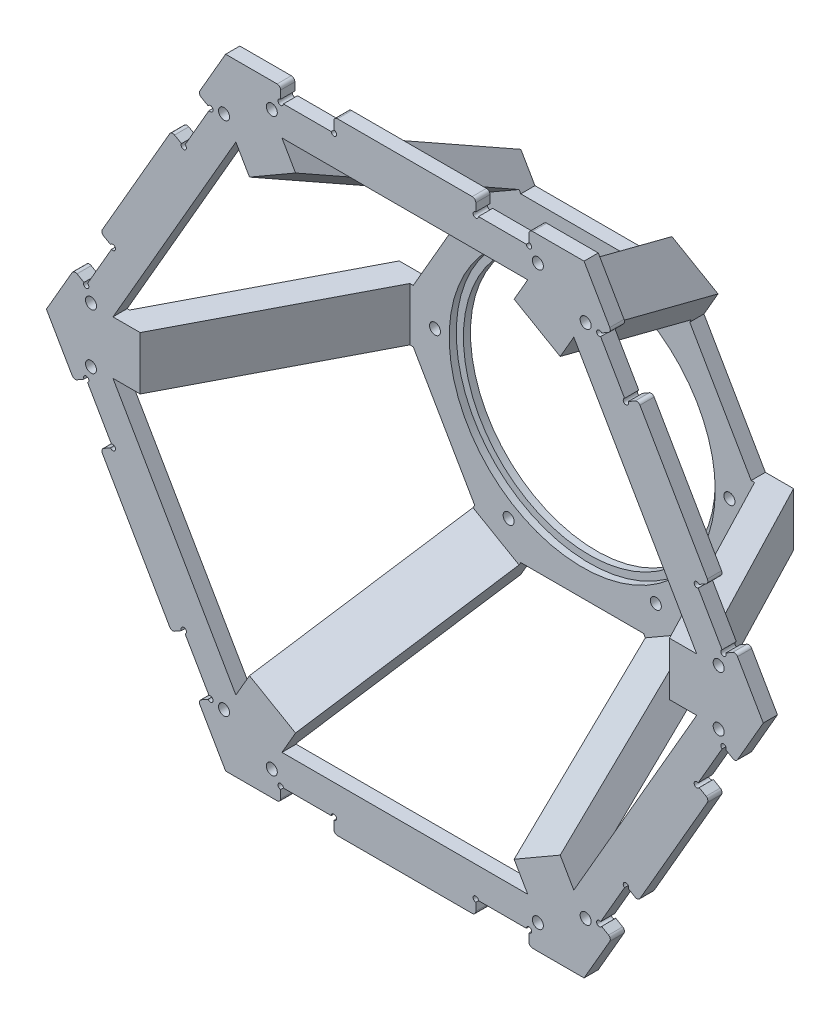
SolidWorks part; units mm, degrees
other "Markup1"
sketch "Sketch62" plane through (-128.5, -128.5, 146.8) normal (-0.0672, -0.6619, 0.7466) x (0.996, 0, 0.0896)
other "Markup2"
sketch "Sketch87" plane through (-128.5, 200.1498, -230) normal (-0.7911, 0.6051, -0.0891) x (-0.112, 0, 0.9937)
ref_plane "Front" through (0, 0, 0) normal (0, 0, 1) x (1, 0, 0)
ref_plane "Top" through (0, 0, 0) normal (0, 1, 0) x (1, 0, 0)
ref_plane "Right" through (0, 0, 0) normal (1, 0, 0) x (0, 0, -1)
sketch "Sketch48" plane through (0, 0, 0) normal (0, 0, 1) x (1, 0, 0)
  line L32 (109.6966, 0) -> (54.8483, 95)
  line L33 (54.8483, 95) -> (-54.8483, 95)
  line L34 (-54.8483, 95) -> (-109.6966, 0)
  line L69 (-109.6966, 0) -> (-54.8483, -95)
  line L70 (-54.8483, -95) -> (54.8483, -95)
  line L71 (54.8483, -95) -> (109.6966, 0)
  circle A2 centre (0, 0) radius 35.5
  circle A13 centre (0, 0) radius 95 construction
  dimension "D1" = 190
  dimension "D8" = 71
extrude "Boss-Extrude15" add sketch "Sketch48" along normal blind 4 separate body
sketch "Sketch88" plane through (0, 0, 4) normal (0, 0, 1) x (1, 0, 0)
  line L0 (0, 0) -> (0, 98.5261) construction
  line L1 (20, 87.5) -> (35, 87.5)
  line L2 (20, 87.5) -> (20, 83.5)
  line L3 (20, 83.5) -> (35, 83.5)
  line L4 (35, 87.5) -> (35, 83.5)
  line L5 (-35, 87.5) -> (-35, 83.5)
  line L6 (-20, 83.5) -> (-35, 83.5)
  line L7 (-20, 87.5) -> (-20, 83.5)
  line L8 (-20, 87.5) -> (-35, 87.5)
  line L9 (58.2772, 74.0609) -> (54.8131, 72.0609)
  line L10 (62.3131, 59.0705) -> (54.8131, 72.0609)
  line L11 (65.7772, 61.0705) -> (62.3131, 59.0705)
  line L12 (65.7772, 61.0705) -> (58.2772, 74.0609)
  line L13 (85.7772, 26.4295) -> (82.3131, 24.4295)
  line L14 (85.7772, 26.4295) -> (93.2772, 13.4391)
  line L15 (93.2772, 13.4391) -> (89.8131, 11.4391)
  line L16 (82.3131, 24.4295) -> (89.8131, 11.4391)
  line L17 (93.2772, -13.4391) -> (89.8131, -11.4391)
  line L18 (82.3131, -24.4295) -> (89.8131, -11.4391)
  line L19 (85.7772, -26.4295) -> (82.3131, -24.4295)
  line L20 (85.7772, -26.4295) -> (93.2772, -13.4391)
  line L21 (65.7772, -61.0705) -> (62.3131, -59.0705)
  line L22 (65.7772, -61.0705) -> (58.2772, -74.0609)
  line L23 (58.2772, -74.0609) -> (54.8131, -72.0609)
  line L24 (62.3131, -59.0705) -> (54.8131, -72.0609)
  line L25 (35, -87.5) -> (35, -83.5)
  line L26 (20, -83.5) -> (35, -83.5)
  line L27 (20, -87.5) -> (20, -83.5)
  line L28 (20, -87.5) -> (35, -87.5)
  line L29 (-20, -87.5) -> (-20, -83.5)
  line L30 (-20, -87.5) -> (-35, -87.5)
  line L31 (-35, -87.5) -> (-35, -83.5)
  line L32 (-20, -83.5) -> (-35, -83.5)
  line L33 (-58.2772, -74.0609) -> (-54.8131, -72.0609)
  line L34 (-62.3131, -59.0705) -> (-54.8131, -72.0609)
  line L35 (-65.7772, -61.0705) -> (-62.3131, -59.0705)
  line L36 (-65.7772, -61.0705) -> (-58.2772, -74.0609)
  line L37 (-85.7772, -26.4295) -> (-82.3131, -24.4295)
  line L38 (-85.7772, -26.4295) -> (-93.2772, -13.4391)
  line L39 (-93.2772, -13.4391) -> (-89.8131, -11.4391)
  line L40 (-82.3131, -24.4295) -> (-89.8131, -11.4391)
  line L41 (-93.2772, 13.4391) -> (-89.8131, 11.4391)
  line L42 (-82.3131, 24.4295) -> (-89.8131, 11.4391)
  line L43 (-85.7772, 26.4295) -> (-82.3131, 24.4295)
  line L44 (-85.7772, 26.4295) -> (-93.2772, 13.4391)
  line L45 (-65.7772, 61.0705) -> (-62.3131, 59.0705)
  line L46 (-65.7772, 61.0705) -> (-58.2772, 74.0609)
  line L47 (-58.2772, 74.0609) -> (-54.8131, 72.0609)
  line L48 (-62.3131, 59.0705) -> (-54.8131, 72.0609)
  line L49 (0, 0) -> (-53.5159, 0) construction
  circle A0 centre (-37.5, 80.5) radius 1.55
  circle A1 centre (37.5, 80.5) radius 1.55
  circle A2 centre (50.965, 72.726) radius 1.55
  circle A3 centre (88.465, 7.774) radius 1.55
  circle A4 centre (88.465, -7.774) radius 1.55
  circle A5 centre (50.965, -72.726) radius 1.55
  circle A6 centre (37.5, -80.5) radius 1.55
  circle A7 centre (-37.5, -80.5) radius 1.55
  circle A8 centre (-50.965, -72.726) radius 1.55
  circle A9 centre (-88.465, -7.774) radius 1.55
  circle A10 centre (-88.465, 7.774) radius 1.55
  circle A11 centre (-50.965, 72.726) radius 1.55
  point P7 (27.5, 83.5)
  point P14 (-27.5, 83.5)
  point P55 (0, 0)
  dimension "D6" = 3
  dimension "D7" = 3.1
  dimension "D8" = 10
  dimension "D1" = 4
  dimension "D2" = 15
  dimension "D3" = 55
  dimension "D4" = 87.5
  dimension "D5" = 6
  dimension "D9" = 6
extrude "Cut-Extrude1" cut sketch "Sketch88" against normal through all
sketch "Sketch89" plane through (0, 0, 4) normal (0, 0, 1) x (1, 0, 0)
  circle A0 centre (0, 0) radius 37.5
  dimension "D1" = 75
extrude "Cut-Extrude2" cut sketch "Sketch89" against normal blind 2
sketch "Sketch90" plane through (0, 0, 4) normal (0, 0, 1) x (1, 0, 0)
  line L2 (0, 0) -> (0, 110.1203) construction
  line L3 (0, 0) -> (49.6986, 0) construction
  circle A1 centre (-35, 83.5) radius 0.75
  circle A3 centre (-20, 83.5) radius 0.75
  circle A4 centre (20, 83.5) radius 0.75
  circle A6 centre (35, 83.5) radius 0.75
  circle A9 centre (54.8131, 72.0609) radius 0.75
  circle A11 centre (62.3131, 59.0705) radius 0.75
  circle A13 centre (82.3131, 24.4295) radius 0.75
  circle A15 centre (89.8131, 11.4391) radius 0.75
  circle A17 centre (89.8131, -11.4391) radius 0.75
  circle A19 centre (82.3131, -24.4295) radius 0.75
  circle A21 centre (62.3131, -59.0705) radius 0.75
  circle A23 centre (54.8131, -72.0609) radius 0.75
  circle A25 centre (35, -83.5) radius 0.75
  circle A27 centre (20, -83.5) radius 0.75
  circle A29 centre (-20, -83.5) radius 0.75
  circle A31 centre (-35, -83.5) radius 0.75
  circle A33 centre (-54.8131, -72.0609) radius 0.75
  circle A35 centre (-62.3131, -59.0705) radius 0.75
  circle A37 centre (-82.3131, -24.4295) radius 0.75
  circle A39 centre (-89.8131, -11.4391) radius 0.75
  circle A41 centre (-89.8131, 11.4391) radius 0.75
  circle A43 centre (-82.3131, 24.4295) radius 0.75
  circle A45 centre (-62.3131, 59.0705) radius 0.75
  circle A47 centre (-54.8131, 72.0609) radius 0.75
  circle A48 centre (41.5, 0) radius 1.55
  circle A49 centre (20.75, -35.9401) radius 1.55
  circle A50 centre (-20.75, -35.9401) radius 1.55
  circle A51 centre (-41.5, 0) radius 1.55
  circle A52 centre (-20.75, 35.9401) radius 1.55
  circle A53 centre (20.75, 35.9401) radius 1.55
  dimension "D1" = 1.5
  dimension "D3" = 41.5
  dimension "D4" = 3.1
  dimension "D2" = 6
  dimension "D5" = 6
extrude "Cut-Extrude3" cut sketch "Sketch90" against normal through all
sketch "Sketch91" plane through (0, 0, 4) normal (0, 0, 1) x (1, 0, 0)
  line L0 (-43.3013, 75) -> (-86.6025, 0) construction
  line L1 (43.3013, 75) -> (-43.3013, 75) construction
  line L2 (-25.9808, 45) -> (-51.9615, 0) construction
  line L3 (25.9808, 45) -> (-25.9808, 45) construction
  line L4 (30.3109, 42.5) -> (41.8579, 62.5)
  line L5 (21.6506, 47.5) -> (33.1976, 67.5)
  line L6 (51.9615, -5) -> (75.0555, -5)
  line L7 (30.3109, -37.5) -> (47.6314, -7.5)
  line L8 (47.6314, 7.5) -> (30.3109, 37.5)
  line L9 (17.3205, 45) -> (-17.3205, 45)
  line L10 (-30.3109, 37.5) -> (-47.6314, 7.5)
  line L11 (-47.6314, -7.5) -> (-30.3109, -37.5)
  line L12 (-17.3205, -45) -> (17.3205, -45)
  line L13 (43.3013, -75) -> (86.6025, 0)
  line L14 (86.6025, 0) -> (43.3013, 75)
  line L15 (43.3013, 75) -> (-43.3013, 75)
  line L16 (-43.3013, 75) -> (-86.6025, 0)
  line L17 (-86.6025, 0) -> (-43.3013, -75)
  line L18 (-43.3013, -75) -> (43.3013, -75)
  line L19 (50.5181, -62.5) -> (79.3857, -12.5)
  line L20 (79.3857, 12.5) -> (50.5181, 62.5)
  line L21 (28.8675, 75) -> (-28.8675, 75)
  line L22 (-50.5181, 62.5) -> (-79.3857, 12.5)
  line L23 (-79.3857, -12.5) -> (-50.5181, -62.5)
  line L24 (-28.8675, -75) -> (28.8675, -75)
  line L25 (-25.9808, 45) -> (-43.3013, 75) construction
  line L26 (-30.3109, 42.5) -> (-41.8579, 62.5)
  line L27 (-21.6506, 47.5) -> (-33.1976, 67.5)
  line L28 (-30.3109, 42.5) -> (-47.6314, 72.5) construction
  line L29 (-21.6506, 47.5) -> (-38.9711, 77.5) construction
  line L30 (51.9615, 5) -> (75.0555, 5)
  line L31 (21.6506, -47.5) -> (33.1976, -67.5)
  line L32 (30.3109, -42.5) -> (41.8579, -62.5)
  line L33 (-30.3109, -42.5) -> (-41.8579, -62.5)
  line L34 (-21.6506, -47.5) -> (-33.1976, -67.5)
  line L35 (-51.9615, 5) -> (-75.0555, 5)
  line L36 (-51.9615, -5) -> (-75.0555, -5)
  line L37 (86.6025, 0) -> (43.3013, 75) construction
  line L38 (51.9615, 0) -> (25.9808, 45) construction
  line L39 (43.3013, -75) -> (86.6025, 0) construction
  line L40 (25.9808, -45) -> (51.9615, 0) construction
  line L41 (-25.9808, -45) -> (25.9808, -45) construction
  line L42 (-43.3013, -75) -> (43.3013, -75) construction
  line L43 (-51.9615, 0) -> (-25.9808, -45) construction
  line L44 (-86.6025, 0) -> (-43.3013, -75) construction
  arc A0 (-41.8579, 62.5) -> (-50.5181, 62.5) centre (-46.188, 60) ccw
  arc A1 (-30.3109, 42.5) -> (-30.3109, 37.5) centre (-34.641, 40) cw
  arc A2 (-21.6506, 47.5) -> (-17.3205, 45) centre (-17.3205, 50) ccw
  arc A3 (-33.1976, 67.5) -> (-28.8675, 75) centre (-28.8675, 70) cw
  arc A4 (41.8579, 62.5) -> (50.5181, 62.5) centre (46.188, 60) cw
  arc A5 (30.3109, 42.5) -> (30.3109, 37.5) centre (34.641, 40) ccw
  arc A6 (21.6506, 47.5) -> (17.3205, 45) centre (17.3205, 50) cw
  arc A7 (33.1976, 67.5) -> (28.8675, 75) centre (28.8675, 70) ccw
  arc A8 (75.0555, -5) -> (79.3857, -12.5) centre (75.0555, -10) cw
  arc A9 (51.9615, -5) -> (47.6314, -7.5) centre (51.9615, -10) ccw
  arc A10 (51.9615, 5) -> (47.6314, 7.5) centre (51.9615, 10) cw
  arc A11 (75.0555, 5) -> (79.3857, 12.5) centre (75.0555, 10) ccw
  arc A12 (33.1976, -67.5) -> (28.8675, -75) centre (28.8675, -70) cw
  arc A13 (21.6506, -47.5) -> (17.3205, -45) centre (17.3205, -50) ccw
  arc A14 (30.3109, -42.5) -> (30.3109, -37.5) centre (34.641, -40) cw
  arc A15 (41.8579, -62.5) -> (50.5181, -62.5) centre (46.188, -60) ccw
  arc A16 (-41.8579, -62.5) -> (-50.5181, -62.5) centre (-46.188, -60) cw
  arc A17 (-30.3109, -42.5) -> (-30.3109, -37.5) centre (-34.641, -40) ccw
  arc A18 (-21.6506, -47.5) -> (-17.3205, -45) centre (-17.3205, -50) cw
  arc A19 (-33.1976, -67.5) -> (-28.8675, -75) centre (-28.8675, -70) ccw
  arc A20 (-75.0555, 5) -> (-79.3857, 12.5) centre (-75.0555, 10) cw
  arc A21 (-51.9615, 5) -> (-47.6314, 7.5) centre (-51.9615, 10) ccw
  arc A22 (-51.9615, -5) -> (-47.6314, -7.5) centre (-51.9615, -10) cw
  arc A23 (-75.0555, -5) -> (-79.3857, -12.5) centre (-75.0555, -10) ccw
  dimension "D5" = 5
  dimension "D1" = 20
  dimension "D2" = 30
  dimension "D3" = 5
  dimension "D4" = 5
  dimension "D6" = 6
extrude "Cut-Extrude5" cut sketch "Sketch91" against normal through all
sketch "Sketch92" plane through (0, 0, 4) normal (0, 0, 1) x (1, 0, 0)
  line L0 (50.5181, -87.5) -> (101.0363, 0)
  line L1 (101.0363, 0) -> (50.5181, 87.5)
  line L2 (50.5181, 87.5) -> (-50.5181, 87.5)
  line L3 (-50.5181, 87.5) -> (-101.0363, 0)
  line L4 (-101.0363, 0) -> (-50.5181, -87.5)
  line L5 (-50.5181, -87.5) -> (50.5181, -87.5)
  line L6 (54.8483, -95) -> (109.6966, 0)
  line L7 (109.6966, 0) -> (54.8483, 95)
  line L8 (54.8483, 95) -> (-54.8483, 95)
  line L9 (-54.8483, 95) -> (-109.6966, 0)
  line L10 (-109.6966, 0) -> (-54.8483, -95)
  line L11 (-54.8483, -95) -> (54.8483, -95)
  line L12 (54.8483, -95) -> (109.6966, 0)
  line L13 (109.6966, 0) -> (54.8483, 95)
  line L14 (54.8483, 95) -> (-54.8483, 95)
  line L15 (-54.8483, 95) -> (-109.6966, 0)
  line L16 (-109.6966, 0) -> (-54.8483, -95)
  line L17 (-54.8483, -95) -> (54.8483, -95)
  dimension "D1" = 0
  dimension "D2" = 7.5
extrude "Cut-Extrude6" cut sketch "Sketch92" against normal through all
fillet "Fillet1" radius 1 24 edges at (-93.2772, 13.4391, 2) (-85.7772, 26.4295, 2) (-65.7772, 61.0705, 2) (-58.2772, 74.0609, 2) (-58.2772, -74.0609, 2) (-65.7772, -61.0705, 2) (-85.7772, -26.4295, 2) (-93.2772, -13.4391, 2) (35, -87.5, 2) (20, -87.5, 2) (-20, -87.5, 2) (-35, -87.5, 2) (93.2772, -13.4391, 2) (85.7772, -26.4295, 2) (65.7772, -61.0705, 2) (58.2772, -74.0609, 2) (58.2772, 74.0609, 2) (65.7772, 61.0705, 2) (85.7772, 26.4295, 2) (93.2772, 13.4391, 2) (-20, 87.5, 2) (35, 87.5, 2) (20, 87.5, 2) (-35, 87.5, 2)
ref_plane "Plane1" through (0, 0, 54) normal (0, 0, 1) x (1, 0, 0)
sketch "Sketch93" plane through (0, 0, 54) normal (0, 0, 1) x (1, 0, 0)
  line L0 (28.8675, 75) -> (-28.8675, 75) construction
  line L1 (-43.3013, 75) -> (-86.6025, 0)
  line L2 (-86.6025, 0) -> (-43.3013, -75)
  line L3 (-43.3013, -75) -> (43.3013, -75)
  line L4 (43.3013, -75) -> (86.6025, 0)
  line L5 (86.6025, 0) -> (43.3013, 75)
  line L6 (43.3013, 75) -> (-43.3013, 75)
  line L54 (-90.4626, 11.8141) -> (-92.4112, 12.9391)
  line L55 (-93.7772, 12.5731) -> (-101.0363, 0)
  line L56 (-101.0363, 0) -> (-93.7772, -12.5731)
  line L57 (-92.4112, -12.9391) -> (-90.4626, -11.8141)
  line L58 (-89.4381, -12.0886) -> (-82.6881, -23.78)
  line L59 (-82.9626, -24.8045) -> (-84.9112, -25.9295)
  line L60 (-85.2772, -27.2955) -> (-66.2772, -60.2045)
  line L61 (-64.9112, -60.5705) -> (-62.9626, -59.4455)
  line L62 (-61.9381, -59.72) -> (-55.1881, -71.4114)
  line L63 (-55.4626, -72.4359) -> (-57.4112, -73.5609)
  line L64 (-57.7772, -74.9269) -> (-50.5181, -87.5)
  line L65 (-50.5181, -87.5) -> (-36, -87.5)
  line L66 (-35, -86.5) -> (-35, -84.25)
  line L67 (-34.25, -83.5) -> (-20.75, -83.5)
  line L68 (-20, -84.25) -> (-20, -86.5)
  line L69 (-19, -87.5) -> (19, -87.5)
  line L70 (20, -86.5) -> (20, -84.25)
  line L71 (20.75, -83.5) -> (34.25, -83.5)
  line L72 (35, -84.25) -> (35, -86.5)
  line L73 (36, -87.5) -> (50.5181, -87.5)
  line L74 (50.5181, -87.5) -> (57.7772, -74.9269)
  line L75 (57.4112, -73.5609) -> (55.4626, -72.4359)
  line L76 (55.1881, -71.4114) -> (61.9381, -59.72)
  line L77 (62.9626, -59.4455) -> (64.9112, -60.5705)
  line L78 (66.2772, -60.2045) -> (85.2772, -27.2955)
  line L79 (84.9112, -25.9295) -> (82.9626, -24.8045)
  line L80 (82.6881, -23.78) -> (89.4381, -12.0886)
  line L81 (90.4626, -11.8141) -> (92.4112, -12.9391)
  line L82 (93.7772, -12.5731) -> (101.0363, 0)
  line L83 (101.0363, 0) -> (93.7772, 12.5731)
  line L84 (92.4112, 12.9391) -> (90.4626, 11.8141)
  line L85 (89.4381, 12.0886) -> (82.6881, 23.78)
  line L86 (82.9626, 24.8045) -> (84.9112, 25.9295)
  line L87 (85.2772, 27.2955) -> (66.2772, 60.2045)
  line L88 (64.9112, 60.5705) -> (62.9626, 59.4455)
  line L89 (61.9381, 59.72) -> (55.1881, 71.4114)
  line L90 (55.4626, 72.4359) -> (57.4112, 73.5609)
  line L91 (57.7772, 74.9269) -> (50.5181, 87.5)
  line L92 (50.5181, 87.5) -> (36, 87.5)
  line L93 (35, 86.5) -> (35, 84.25)
  line L94 (34.25, 83.5) -> (20.75, 83.5)
  line L95 (20, 84.25) -> (20, 86.5)
  line L96 (19, 87.5) -> (-19, 87.5)
  line L97 (-20, 86.5) -> (-20, 84.25)
  line L98 (-20.75, 83.5) -> (-34.25, 83.5)
  line L99 (-35, 84.25) -> (-35, 86.5)
  line L100 (-36, 87.5) -> (-50.5181, 87.5)
  line L101 (-50.5181, 87.5) -> (-57.7772, 74.9269)
  line L102 (-57.4112, 73.5609) -> (-55.4626, 72.4359)
  line L103 (-55.1881, 71.4114) -> (-61.9381, 59.72)
  line L104 (-62.9626, 59.4455) -> (-64.9112, 60.5705)
  line L105 (-66.2772, 60.2045) -> (-85.2772, 27.2955)
  line L106 (-84.9112, 25.9295) -> (-82.9626, 24.8045)
  line L107 (-82.6881, 23.78) -> (-89.4381, 12.0886)
  line L108 (-90.4626, 11.8141) -> (-92.4112, 12.9391)
  line L109 (-93.7772, 12.5731) -> (-101.0363, 0)
  line L110 (-101.0363, 0) -> (-93.7772, -12.5731)
  line L111 (-92.4112, -12.9391) -> (-90.4626, -11.8141)
  line L112 (-89.4381, -12.0886) -> (-82.6881, -23.78)
  line L113 (-82.9626, -24.8045) -> (-84.9112, -25.9295)
  line L114 (-85.2772, -27.2955) -> (-66.2772, -60.2045)
  line L115 (-64.9112, -60.5705) -> (-62.9626, -59.4455)
  line L116 (-61.9381, -59.72) -> (-55.1881, -71.4114)
  line L117 (-55.4626, -72.4359) -> (-57.4112, -73.5609)
  line L118 (-57.7772, -74.9269) -> (-50.5181, -87.5)
  line L119 (-50.5181, -87.5) -> (-36, -87.5)
  line L120 (-35, -86.5) -> (-35, -84.25)
  line L121 (-34.25, -83.5) -> (-20.75, -83.5)
  line L122 (-20, -84.25) -> (-20, -86.5)
  line L123 (-19, -87.5) -> (19, -87.5)
  line L124 (20, -86.5) -> (20, -84.25)
  line L125 (20.75, -83.5) -> (34.25, -83.5)
  line L126 (35, -84.25) -> (35, -86.5)
  line L127 (36, -87.5) -> (50.5181, -87.5)
  line L128 (50.5181, -87.5) -> (57.7772, -74.9269)
  line L129 (57.4112, -73.5609) -> (55.4626, -72.4359)
  line L130 (55.1881, -71.4114) -> (61.9381, -59.72)
  line L131 (62.9626, -59.4455) -> (64.9112, -60.5705)
  line L132 (66.2772, -60.2045) -> (85.2772, -27.2955)
  line L133 (84.9112, -25.9295) -> (82.9626, -24.8045)
  line L134 (82.6881, -23.78) -> (89.4381, -12.0886)
  line L135 (90.4626, -11.8141) -> (92.4112, -12.9391)
  line L136 (93.7772, -12.5731) -> (101.0363, 0)
  line L137 (101.0363, 0) -> (93.7772, 12.5731)
  line L138 (92.4112, 12.9391) -> (90.4626, 11.8141)
  line L139 (89.4381, 12.0886) -> (82.6881, 23.78)
  line L140 (82.9626, 24.8045) -> (84.9112, 25.9295)
  line L141 (85.2772, 27.2955) -> (66.2772, 60.2045)
  line L142 (64.9112, 60.5705) -> (62.9626, 59.4455)
  line L143 (61.9381, 59.72) -> (55.1881, 71.4114)
  line L144 (55.4626, 72.4359) -> (57.4112, 73.5609)
  line L145 (57.7772, 74.9269) -> (50.5181, 87.5)
  line L146 (50.5181, 87.5) -> (36, 87.5)
  line L147 (35, 86.5) -> (35, 84.25)
  line L148 (34.25, 83.5) -> (20.75, 83.5)
  line L149 (20, 84.25) -> (20, 86.5)
  line L150 (19, 87.5) -> (-19, 87.5)
  line L151 (-20, 86.5) -> (-20, 84.25)
  line L152 (-20.75, 83.5) -> (-34.25, 83.5)
  line L153 (-35, 84.25) -> (-35, 86.5)
  line L154 (-36, 87.5) -> (-50.5181, 87.5)
  line L155 (-50.5181, 87.5) -> (-57.7772, 74.9269)
  line L156 (-57.4112, 73.5609) -> (-55.4626, 72.4359)
  line L157 (-55.1881, 71.4114) -> (-61.9381, 59.72)
  line L158 (-62.9626, 59.4455) -> (-64.9112, 60.5705)
  line L159 (-66.2772, 60.2045) -> (-85.2772, 27.2955)
  line L160 (-84.9112, 25.9295) -> (-82.9626, 24.8045)
  line L161 (-82.6881, 23.78) -> (-89.4381, 12.0886)
  circle A0 centre (-88.465, 7.774) radius 1.55 construction
  circle A1 centre (-88.465, 7.774) radius 1.55
  circle A2 centre (-88.465, -7.774) radius 1.55 construction
  circle A3 centre (-88.465, -7.774) radius 1.55
  circle A10 centre (-37.5, 80.5) radius 1.55
  circle A11 centre (-50.965, 72.726) radius 1.55
  circle A12 centre (50.965, 72.726) radius 1.55
  circle A13 centre (37.5, 80.5) radius 1.55
  circle A14 centre (88.465, -7.774) radius 1.55
  circle A15 centre (88.465, 7.774) radius 1.55
  circle A16 centre (37.5, -80.5) radius 1.55
  circle A17 centre (50.965, -72.726) radius 1.55
  circle A18 centre (-50.965, -72.726) radius 1.55
  circle A19 centre (-37.5, -80.5) radius 1.55
  circle A20 centre (0, 0) radius 75 construction
  arc A48 (-92.4112, 12.9391) -> (-93.7772, 12.5731) centre (-92.9112, 12.0731) ccw
  arc A49 (-93.7772, -12.5731) -> (-92.4112, -12.9391) centre (-92.9112, -12.0731) ccw
  arc A50 (-89.4381, -12.0886) -> (-90.4626, -11.8141) centre (-89.8131, -11.4391) ccw
  arc A51 (-82.9626, -24.8045) -> (-82.6881, -23.78) centre (-82.3131, -24.4295) ccw
  arc A52 (-84.9112, -25.9295) -> (-85.2772, -27.2955) centre (-84.4112, -26.7955) ccw
  arc A53 (-66.2772, -60.2045) -> (-64.9112, -60.5705) centre (-65.4112, -59.7045) ccw
  arc A54 (-61.9381, -59.72) -> (-62.9626, -59.4455) centre (-62.3131, -59.0705) ccw
  arc A55 (-55.4626, -72.4359) -> (-55.1881, -71.4114) centre (-54.8131, -72.0609) ccw
  arc A56 (-57.4112, -73.5609) -> (-57.7772, -74.9269) centre (-56.9112, -74.4269) ccw
  arc A57 (-36, -87.5) -> (-35, -86.5) centre (-36, -86.5) ccw
  arc A58 (-34.25, -83.5) -> (-35, -84.25) centre (-35, -83.5) ccw
  arc A59 (-20, -84.25) -> (-20.75, -83.5) centre (-20, -83.5) ccw
  arc A60 (-20, -86.5) -> (-19, -87.5) centre (-19, -86.5) ccw
  arc A61 (19, -87.5) -> (20, -86.5) centre (19, -86.5) ccw
  arc A62 (20.75, -83.5) -> (20, -84.25) centre (20, -83.5) ccw
  arc A63 (35, -84.25) -> (34.25, -83.5) centre (35, -83.5) ccw
  arc A64 (35, -86.5) -> (36, -87.5) centre (36, -86.5) ccw
  arc A65 (57.7772, -74.9269) -> (57.4112, -73.5609) centre (56.9112, -74.4269) ccw
  arc A66 (55.1881, -71.4114) -> (55.4626, -72.4359) centre (54.8131, -72.0609) ccw
  arc A67 (62.9626, -59.4455) -> (61.9381, -59.72) centre (62.3131, -59.0705) ccw
  arc A68 (64.9112, -60.5705) -> (66.2772, -60.2045) centre (65.4112, -59.7045) ccw
  arc A69 (85.2772, -27.2955) -> (84.9112, -25.9295) centre (84.4112, -26.7955) ccw
  arc A70 (82.6881, -23.78) -> (82.9626, -24.8045) centre (82.3131, -24.4295) ccw
  arc A71 (90.4626, -11.8141) -> (89.4381, -12.0886) centre (89.8131, -11.4391) ccw
  arc A72 (92.4112, -12.9391) -> (93.7772, -12.5731) centre (92.9112, -12.0731) ccw
  arc A73 (93.7772, 12.5731) -> (92.4112, 12.9391) centre (92.9112, 12.0731) ccw
  arc A74 (89.4381, 12.0886) -> (90.4626, 11.8141) centre (89.8131, 11.4391) ccw
  arc A75 (82.9626, 24.8045) -> (82.6881, 23.78) centre (82.3131, 24.4295) ccw
  arc A76 (84.9112, 25.9295) -> (85.2772, 27.2955) centre (84.4112, 26.7955) ccw
  arc A77 (66.2772, 60.2045) -> (64.9112, 60.5705) centre (65.4112, 59.7045) ccw
  arc A78 (61.9381, 59.72) -> (62.9626, 59.4455) centre (62.3131, 59.0705) ccw
  arc A79 (55.4626, 72.4359) -> (55.1881, 71.4114) centre (54.8131, 72.0609) ccw
  arc A80 (57.4112, 73.5609) -> (57.7772, 74.9269) centre (56.9112, 74.4269) ccw
  arc A81 (36, 87.5) -> (35, 86.5) centre (36, 86.5) ccw
  arc A82 (34.25, 83.5) -> (35, 84.25) centre (35, 83.5) ccw
  arc A83 (20, 84.25) -> (20.75, 83.5) centre (20, 83.5) ccw
  arc A84 (20, 86.5) -> (19, 87.5) centre (19, 86.5) ccw
  arc A85 (-19, 87.5) -> (-20, 86.5) centre (-19, 86.5) ccw
  arc A86 (-20.75, 83.5) -> (-20, 84.25) centre (-20, 83.5) ccw
  arc A87 (-35, 84.25) -> (-34.25, 83.5) centre (-35, 83.5) ccw
  arc A88 (-35, 86.5) -> (-36, 87.5) centre (-36, 86.5) ccw
  arc A89 (-57.7772, 74.9269) -> (-57.4112, 73.5609) centre (-56.9112, 74.4269) ccw
  arc A90 (-55.1881, 71.4114) -> (-55.4626, 72.4359) centre (-54.8131, 72.0609) ccw
  arc A91 (-62.9626, 59.4455) -> (-61.9381, 59.72) centre (-62.3131, 59.0705) ccw
  arc A92 (-64.9112, 60.5705) -> (-66.2772, 60.2045) centre (-65.4112, 59.7045) ccw
  arc A93 (-85.2772, 27.2955) -> (-84.9112, 25.9295) centre (-84.4112, 26.7955) ccw
  arc A94 (-82.6881, 23.78) -> (-82.9626, 24.8045) centre (-82.3131, 24.4295) ccw
  arc A95 (-90.4626, 11.8141) -> (-89.4381, 12.0886) centre (-89.8131, 11.4391) ccw
  arc A96 (-92.4112, 12.9391) -> (-93.7772, 12.5731) centre (-92.9112, 12.0731) ccw
  arc A97 (-93.7772, -12.5731) -> (-92.4112, -12.9391) centre (-92.9112, -12.0731) ccw
  arc A98 (-89.4381, -12.0886) -> (-90.4626, -11.8141) centre (-89.8131, -11.4391) ccw
  arc A99 (-82.9626, -24.8045) -> (-82.6881, -23.78) centre (-82.3131, -24.4295) ccw
  arc A100 (-84.9112, -25.9295) -> (-85.2772, -27.2955) centre (-84.4112, -26.7955) ccw
  arc A101 (-66.2772, -60.2045) -> (-64.9112, -60.5705) centre (-65.4112, -59.7045) ccw
  arc A102 (-61.9381, -59.72) -> (-62.9626, -59.4455) centre (-62.3131, -59.0705) ccw
  arc A103 (-55.4626, -72.4359) -> (-55.1881, -71.4114) centre (-54.8131, -72.0609) ccw
  arc A104 (-57.4112, -73.5609) -> (-57.7772, -74.9269) centre (-56.9112, -74.4269) ccw
  arc A105 (-36, -87.5) -> (-35, -86.5) centre (-36, -86.5) ccw
  arc A106 (-34.25, -83.5) -> (-35, -84.25) centre (-35, -83.5) ccw
  arc A107 (-20, -84.25) -> (-20.75, -83.5) centre (-20, -83.5) ccw
  arc A108 (-20, -86.5) -> (-19, -87.5) centre (-19, -86.5) ccw
  arc A109 (19, -87.5) -> (20, -86.5) centre (19, -86.5) ccw
  arc A110 (20.75, -83.5) -> (20, -84.25) centre (20, -83.5) ccw
  arc A111 (35, -84.25) -> (34.25, -83.5) centre (35, -83.5) ccw
  arc A112 (35, -86.5) -> (36, -87.5) centre (36, -86.5) ccw
  arc A113 (57.7772, -74.9269) -> (57.4112, -73.5609) centre (56.9112, -74.4269) ccw
  arc A114 (55.1881, -71.4114) -> (55.4626, -72.4359) centre (54.8131, -72.0609) ccw
  arc A115 (62.9626, -59.4455) -> (61.9381, -59.72) centre (62.3131, -59.0705) ccw
  arc A116 (64.9112, -60.5705) -> (66.2772, -60.2045) centre (65.4112, -59.7045) ccw
  arc A117 (85.2772, -27.2955) -> (84.9112, -25.9295) centre (84.4112, -26.7955) ccw
  arc A118 (82.6881, -23.78) -> (82.9626, -24.8045) centre (82.3131, -24.4295) ccw
  arc A119 (90.4626, -11.8141) -> (89.4381, -12.0886) centre (89.8131, -11.4391) ccw
  arc A120 (92.4112, -12.9391) -> (93.7772, -12.5731) centre (92.9112, -12.0731) ccw
  arc A121 (93.7772, 12.5731) -> (92.4112, 12.9391) centre (92.9112, 12.0731) ccw
  arc A122 (89.4381, 12.0886) -> (90.4626, 11.8141) centre (89.8131, 11.4391) ccw
  arc A123 (82.9626, 24.8045) -> (82.6881, 23.78) centre (82.3131, 24.4295) ccw
  arc A124 (84.9112, 25.9295) -> (85.2772, 27.2955) centre (84.4112, 26.7955) ccw
  arc A125 (66.2772, 60.2045) -> (64.9112, 60.5705) centre (65.4112, 59.7045) ccw
  arc A126 (61.9381, 59.72) -> (62.9626, 59.4455) centre (62.3131, 59.0705) ccw
  arc A127 (55.4626, 72.4359) -> (55.1881, 71.4114) centre (54.8131, 72.0609) ccw
  arc A128 (57.4112, 73.5609) -> (57.7772, 74.9269) centre (56.9112, 74.4269) ccw
  arc A129 (36, 87.5) -> (35, 86.5) centre (36, 86.5) ccw
  arc A130 (34.25, 83.5) -> (35, 84.25) centre (35, 83.5) ccw
  arc A131 (20, 84.25) -> (20.75, 83.5) centre (20, 83.5) ccw
  arc A132 (20, 86.5) -> (19, 87.5) centre (19, 86.5) ccw
  arc A133 (-19, 87.5) -> (-20, 86.5) centre (-19, 86.5) ccw
  arc A134 (-20.75, 83.5) -> (-20, 84.25) centre (-20, 83.5) ccw
  arc A135 (-35, 84.25) -> (-34.25, 83.5) centre (-35, 83.5) ccw
  arc A136 (-35, 86.5) -> (-36, 87.5) centre (-36, 86.5) ccw
  arc A137 (-57.7772, 74.9269) -> (-57.4112, 73.5609) centre (-56.9112, 74.4269) ccw
  arc A138 (-55.1881, 71.4114) -> (-55.4626, 72.4359) centre (-54.8131, 72.0609) ccw
  arc A139 (-62.9626, 59.4455) -> (-61.9381, 59.72) centre (-62.3131, 59.0705) ccw
  arc A140 (-64.9112, 60.5705) -> (-66.2772, 60.2045) centre (-65.4112, 59.7045) ccw
  arc A141 (-85.2772, 27.2955) -> (-84.9112, 25.9295) centre (-84.4112, 26.7955) ccw
  arc A142 (-82.6881, 23.78) -> (-82.9626, 24.8045) centre (-82.3131, 24.4295) ccw
  arc A143 (-90.4626, 11.8141) -> (-89.4381, 12.0886) centre (-89.8131, 11.4391) ccw
  dimension "D1" = 0
  dimension "D2" = 6
extrude "Boss-Extrude16" add sketch "Sketch93" against normal blind 4 separate body
sketch "Sketch94" plane through (0, 0, 4) normal (0, 0, 1) x (1, 0, 0)
  line L0 (-17.3205, 45) -> (17.3205, 45) construction
  line L1 (-25.9808, 45) -> (-51.9615, 0)
  line L2 (-51.9615, 0) -> (-25.9808, -45)
  line L3 (-25.9808, -45) -> (25.9808, -45)
  line L4 (25.9808, -45) -> (51.9615, 0)
  line L5 (51.9615, 0) -> (25.9808, 45)
  line L6 (25.9808, 45) -> (-25.9808, 45)
  circle A0 centre (0, 0) radius 45 construction
  circle A1 centre (0, 0) radius 133.0138
extrude "Cut-Extrude8" cut sketch "Sketch94" against normal blind 15
sketch "Sketch95" plane through (0, 0, 0) normal (0, 1, 0) x (1, 0, 0)
  line L1 (-74.6025, -54) -> (-48.5832, -4)
  line L3 (-43.5832, 0) -> (-55.5832, 0)
  line L4 (-55.5832, 0) -> (-81.6025, -50)
  line L7 (19.2, -4) -> (22.3, -4) construction
  line L8 (22.3, 0) -> (19.2, 0) construction
  line L9 (-74.6025, -54) -> (-86.6025, -54)
  line L10 (-86.6025, -54) -> (-86.6025, -50)
  line L11 (-89.4381, -50) -> (-82.6881, -50) construction
  line L12 (-86.6025, -50) -> (-81.6025, -50)
  line L13 (-50.4068, -54) -> (50.4068, -54) construction
  line L15 (-48.5832, -4) -> (-43.5832, -4)
  line L16 (-43.5832, -4) -> (-43.5832, 0)
  point P0 (-49.733, -4)
  dimension "D2" = 5
extrude "Boss-Extrude18" add sketch "Sketch95" along normal mid plane 15
pattern_circular "CirPattern1" count 6 over 360 about axis through (0, 0, 0) along (0, 0, 1) of "Boss-Extrude18"
